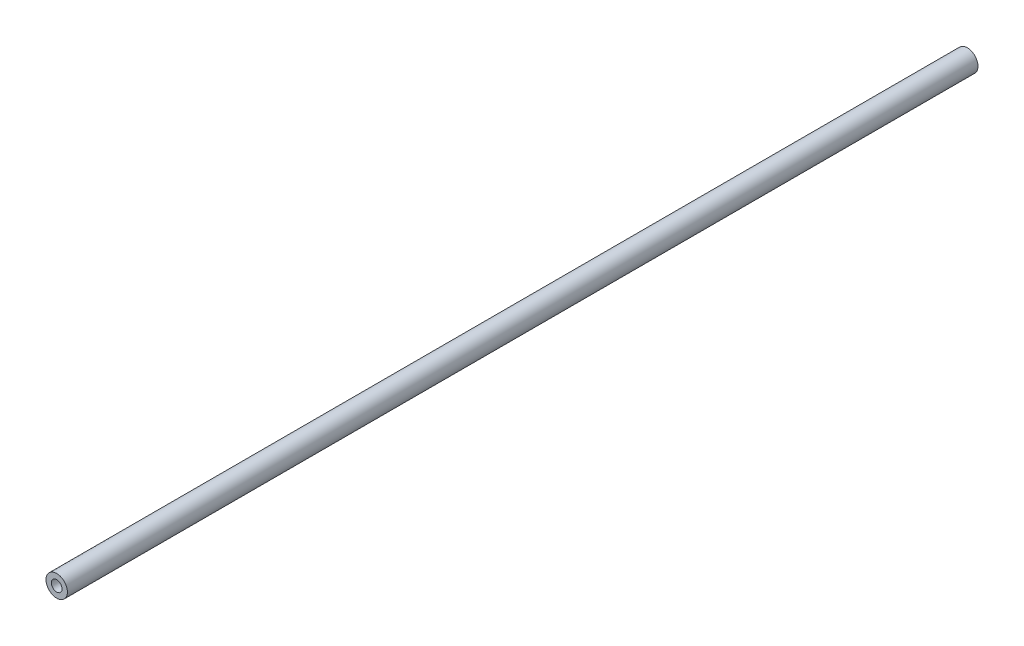
SolidWorks part; units mm, degrees
ref_plane "Front Plane" through (0, 0, 0) normal (0, 0, 1) x (1, 0, 0)
ref_plane "Top Plane" through (0, 0, 0) normal (0, 1, 0) x (1, 0, 0)
ref_plane "Right Plane" through (0, 0, 0) normal (1, 0, 0) x (0, 0, -1)
sketch "Sketch1" plane through (0, 0, 0) normal (0, 0, 1) x (1, 0, 0)
  circle A0 centre (0, 0) radius 1
  circle A1 centre (0, 0) radius 0.5
extrude "Tube" add sketch "Sketch1" along normal blind 85 from offset 42.5
